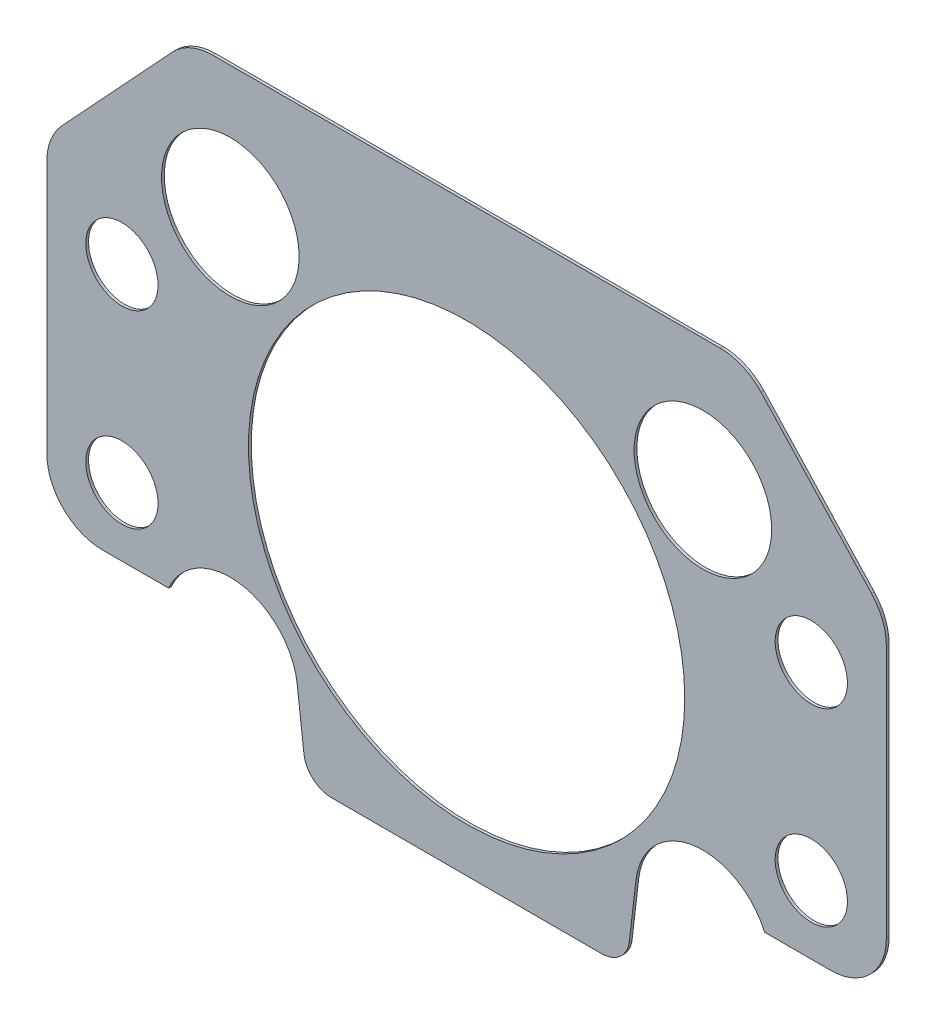
SolidWorks part; units mm, degrees
material "TESNIT BA-R"
ref_plane "Front Plane" through (0, 0, 0) normal (0, 0, 1) x (1, 0, 0)
ref_plane "Top Plane" through (0, 0, 0) normal (0, 1, 0) x (1, 0, 0)
ref_plane "Right Plane" through (0, 0, 0) normal (1, 0, 0) x (0, 0, -1)
sketch "Sketch1" plane through (0, 0, 0) normal (0, 0, 1) x (1, 0, 0)
  line L28 (-2.5617, 115.5) -> (-91.2703, 115.5)
  line L29 (-105.9357, 109.0988) -> (-145.6654, 66.253)
  line L30 (-151, 52.6542) -> (-151, -38.5)
  line L31 (-131, -58.5) -> (-107.2036, -58.5)
  line L32 (-60.9156, -65.4211) -> (-58.5376, -85.6666)
  line L33 (-48.6058, -94.5) -> (48.6058, -94.5)
  line L34 (58.5376, -85.6666) -> (60.9156, -65.4211)
  line L35 (107.2036, -58.5) -> (131, -58.5)
  line L36 (151, -38.5) -> (151, 52.6542)
  line L37 (145.6654, 66.253) -> (105.9357, 109.0988)
  line L38 (91.2703, 115.5) -> (-2.5617, 115.5)
  circle A6 centre (-85, 68.25) radius 24.75
  circle A7 centre (85, 68.25) radius 24.75
  circle A8 centre (124, -34) radius 13
  circle A9 centre (124, 34) radius 13
  arc A20 (-91.2703, 115.5) -> (-105.9357, 109.0988) centre (-91.2703, 95.5) ccw
  arc A21 (-145.6654, 66.253) -> (-151, 52.6542) centre (-131, 52.6542) ccw
  arc A22 (-151, -38.5) -> (-131, -58.5) centre (-131, -38.5) ccw
  arc A23 (-60.9156, -65.4211) -> (-107.2036, -58.5) centre (-85, -68.25) ccw
  arc A24 (-58.5376, -85.6666) -> (-48.6058, -94.5) centre (-48.6058, -84.5) ccw
  arc A25 (48.6058, -94.5) -> (58.5376, -85.6666) centre (48.6058, -84.5) ccw
  arc A26 (107.2036, -58.5) -> (60.9156, -65.4211) centre (85, -68.25) ccw
  arc A27 (131, -58.5) -> (151, -38.5) centre (131, -38.5) ccw
  arc A28 (151, 52.6542) -> (145.6654, 66.253) centre (131, 52.6542) ccw
  arc A29 (105.9357, 109.0988) -> (91.2703, 115.5) centre (91.2703, 95.5) ccw
  circle A30 centre (-124, 34) radius 13
  circle A31 centre (-124, -34) radius 13
  circle A35 centre (0, 0) radius 78.475
extrude "Boss-Extrude1" add sketch "Sketch1" along normal blind 1
